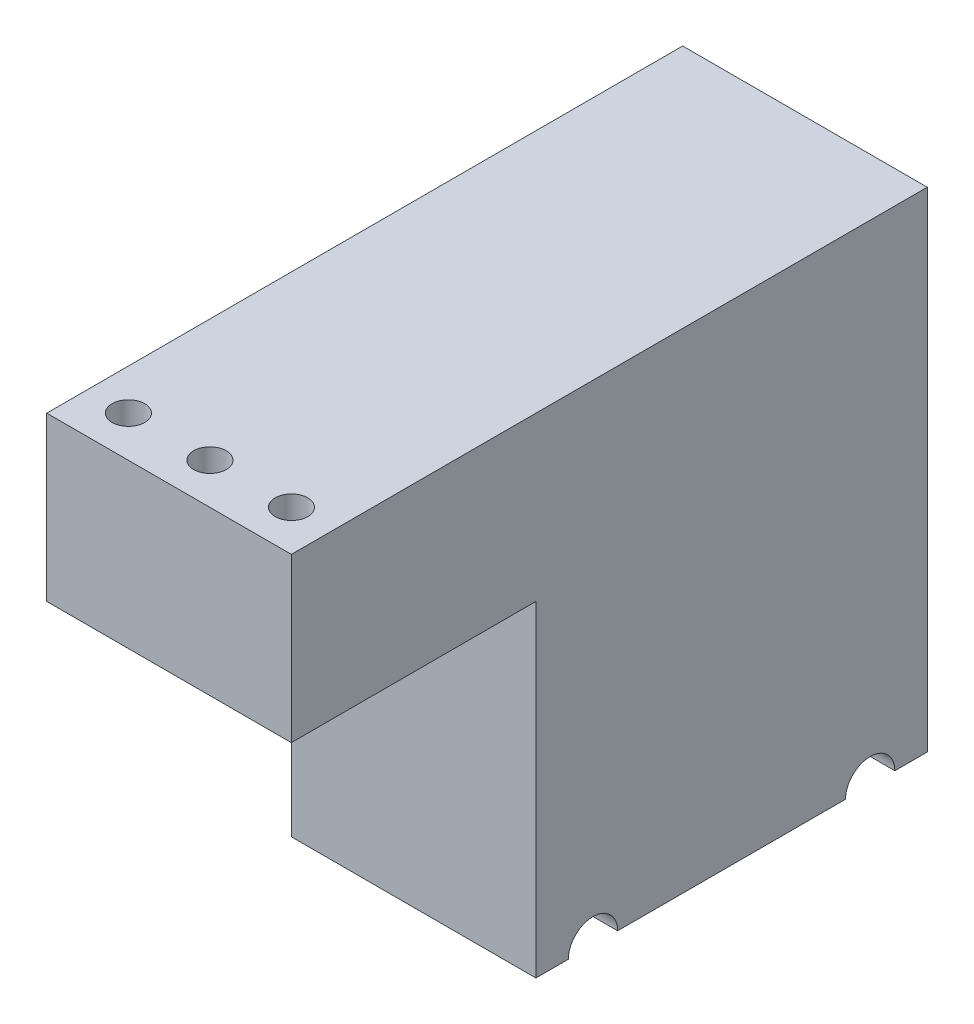
SolidWorks part; units mm, degrees
ref_plane "前视基准面" through (0, 0, 0) normal (0, 0, 1) x (1, 0, 0)
ref_plane "上视基准面" through (0, 0, 0) normal (0, 1, 0) x (1, 0, 0)
ref_plane "右视基准面" through (0, 0, 0) normal (1, 0, 0) x (0, 0, -1)
sketch "草图1" plane through (0, 0, 0) normal (0, 0, 1) x (1, 0, 0)
  line L1 (0, 0) -> (30, 0)
  line L2 (0, 0) -> (0, 95)
  line L3 (0, 95) -> (30, 95)
  line L4 (30, 0) -> (30, 95)
extrude "凸台-拉伸1" add sketch "草图1" along normal blind 48
sketch "草图2" plane through (0, 0, 0) normal (-1, 0, 0) x (0, 0, 1)
  line L1 (48, 95) -> (48, 0) construction
  line L2 (48, 0) -> (0, 0) construction
  circle A0 centre (7, 35) radius 3.005
  circle A1 centre (41, 35) radius 3.005
  circle A2 centre (7, 35) radius 3.025
  circle A3 centre (41, 35) radius 3.025
  dimension "D3" = 6.01
  dimension "D1" = 34
  dimension "D2" = 7
  dimension "D5" = 35
  dimension "D6" = 35
  dimension "D4" = 0.02
extrude "切除-拉伸1" cut sketch "草图2" against normal blind 46
sketch "草图3" plane through (0, 0, 48) normal (0, 0, 1) x (1, 0, 0)
  line L0 (30, 0) -> (30, 95) construction
  line L1 (0, 95) -> (30, 95)
  line L2 (0, 95) -> (0, 75)
  line L3 (0, 75) -> (30, 75)
  line L4 (30, 95) -> (30, 75)
extrude "凸台-拉伸2" add sketch "草图3" along normal blind 30
sketch "草图4" plane through (0, 95, 0) normal (0, 1, 0) x (1, 0, 0)
  line L0 (30, -78) -> (30, 0) construction
  line L1 (0, -78) -> (0, 0) construction
  circle A0 centre (5, -72.9837) radius 2
  circle A1 centre (15, -72.9837) radius 2
  circle A2 centre (25, -72.9837) radius 2
  point P6 (0, 0)
  dimension "D1" = 4
  dimension "D2" = 5
  dimension "D3" = 10
  dimension "D4" = 10
  dimension "D5" = 5
extrude "切除-拉伸2" cut sketch "草图4" against normal blind 5
sketch "草图5" plane through (0, 0, 0) normal (-1, 0, 0) x (0, 0, 1)
  line L0 (0, 95) -> (0, 0) construction
  line L1 (0, 35) -> (48, 35)
  line L2 (0, 35) -> (0, 0)
  line L3 (0, 0) -> (48, 0)
  line L4 (48, 35) -> (48, 0)
extrude "切除-拉伸3" cut sketch "草图5" against normal through all
sketch "草图6" plane through (0, 35, 0) normal (0, -1, 0) x (1, 0, 0)
  line L0 (0, 37.975) -> (0, 10.025) construction
  line L1 (0, 37.975) -> (30, 37.975) construction
  line L3 (30, 10.025) -> (0, 10.025) construction
  circle A0 centre (6, 31.975) radius 2
  circle A1 centre (12, 31.975) radius 2
  circle A2 centre (18, 31.975) radius 2
  circle A3 centre (24, 31.975) radius 2
  circle A4 centre (6, 16.025) radius 2
  circle A5 centre (12, 16.025) radius 2
  circle A6 centre (18, 16.025) radius 2
  circle A7 centre (24, 16.025) radius 2
  point P18 (0, 0)
  point P19 (0, 0)
  point P20 (0, 0)
  point P21 (0, 0)
  point P24 (0, 0)
  point P27 (0, 0)
  dimension "D1" = 4
  dimension "D3" = 6
  dimension "D4" = 6
  dimension "D7" = 6
  dimension "D6" = 6
  dimension "D2" = 6
  dimension "D5" = 6
extrude "切除-拉伸4" cut sketch "草图6" against normal blind 5
